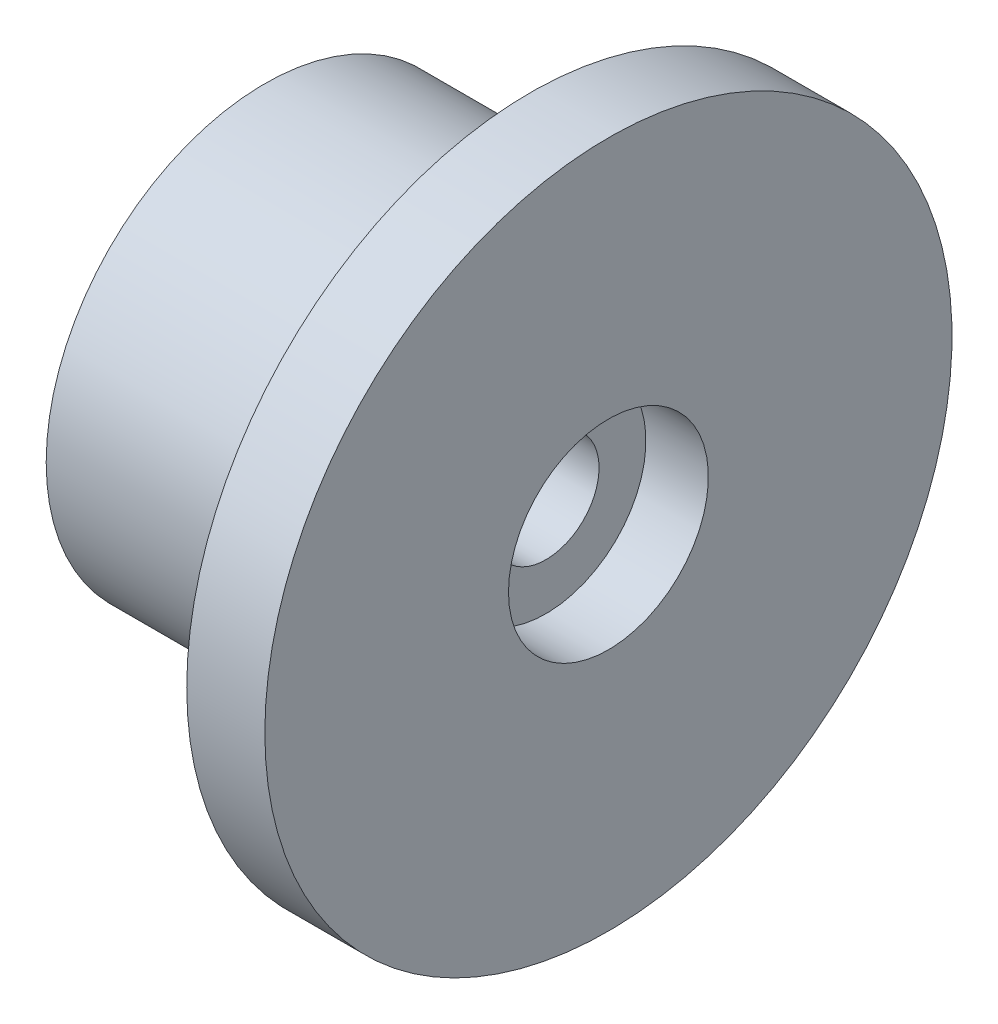
SolidWorks part; units mm, degrees
ref_plane "Front Plane" through (0, 0, 0) normal (0, 0, 1) x (1, 0, 0)
ref_plane "Top Plane" through (0, 0, 0) normal (0, 1, 0) x (1, 0, 0)
ref_plane "Right Plane" through (0, 0, 0) normal (1, 0, 0) x (0, 0, -1)
sketch "Sketch1" plane through (0, 0, 0) normal (0, 0, 1) x (1, 0, 0)
  line L0 (-5, 0) -> (18.5, 0) construction
  line L1 (0, 1.7) -> (0, 7)
  line L2 (0, 7) -> (8.5, 7)
  line L3 (8.5, 7) -> (8.5, 11)
  line L4 (8.5, 11) -> (11, 11)
  line L5 (11, 11) -> (11, 3.2)
  line L6 (11, 3.2) -> (9, 3.2)
  line L7 (9, 3.2) -> (9, 1.7)
  line L8 (9, 1.7) -> (0, 1.7)
revolve "Pin" add sketch "Sketch1" angle 360 about L0
